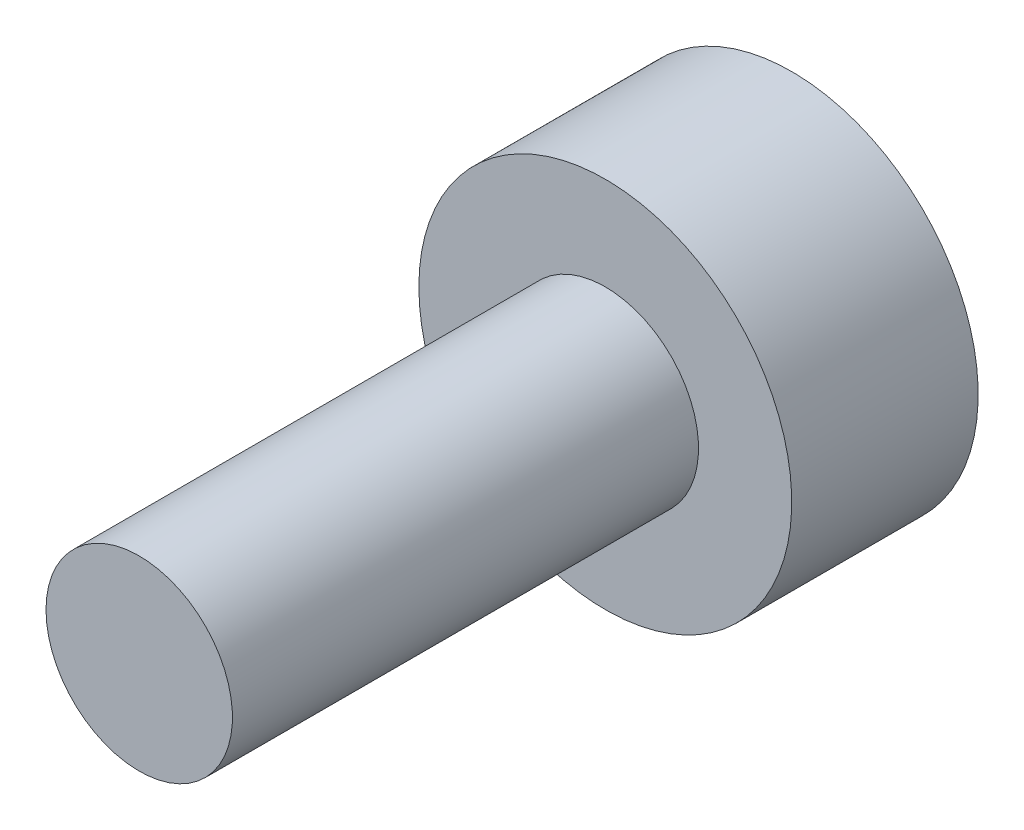
SolidWorks part; units mm, degrees
ref_plane "Płaszczyzna przednia" through (0, 0, 0) normal (0, 0, 1) x (1, 0, 0)
ref_plane "Płaszczyzna górna" through (0, 0, 0) normal (0, 1, 0) x (1, 0, 0)
ref_plane "Płaszczyzna prawa" through (0, 0, 0) normal (1, 0, 0) x (0, 0, -1)
sketch "Sketch1" plane through (0, 0, 0) normal (0, 1, 0) x (1, 0, 0)
  line L0 (0, 0) -> (1, 0)
  line L1 (1, 0) -> (1, 5)
  line L2 (1, 5) -> (2, 5)
  line L3 (2, 5) -> (2, 7)
  line L4 (2, 7) -> (0, 7)
  line L5 (0, 7) -> (0, 0)
  point P9 (1.2067, 3.348)
  point P10 (2.5114, 3.4883)
  dimension "D1" = 2
  dimension "D2" = 1
  dimension "D3" = 2
  dimension "D4" = 5
revolve "Revolve1" add sketch "Sketch1" angle 360 about L5
sketch "Sketch2" plane through (0, 0, -7) normal (0, 0, -1) x (-1, 0, 0)
  line L1 (0.433, 0.75) -> (-0.433, 0.75)
  line L2 (-0.433, 0.75) -> (-0.866, 0)
  line L3 (-0.866, 0) -> (-0.433, -0.75)
  line L4 (-0.433, -0.75) -> (0.433, -0.75)
  line L5 (0.433, -0.75) -> (0.866, 0)
  line L6 (0.866, 0) -> (0.433, 0.75)
  circle A0 centre (0, 0) radius 0.75 construction
  dimension "D1" = 1.5
extrude "Cut-Extrude1" cut sketch "Sketch2" against normal blind 1.2
